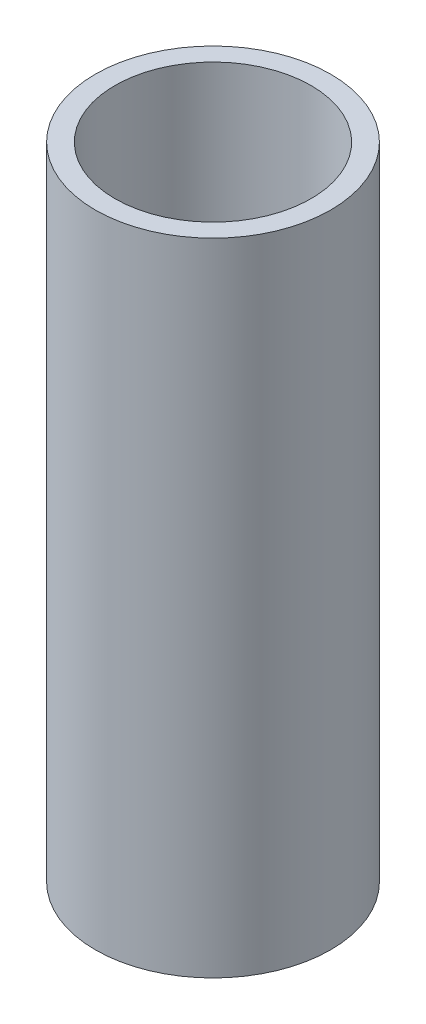
SolidWorks part; units mm, degrees
ref_plane "Front Plane" through (0, 0, 0) normal (0, 0, 1) x (1, 0, 0)
ref_plane "Top Plane" through (0, 0, 0) normal (0, 1, 0) x (1, 0, 0)
ref_plane "Right Plane" through (0, 0, 0) normal (1, 0, 0) x (0, 0, -1)
sketch "Sketch1" plane through (0, 0, 0) normal (0, 1, 0) x (1, 0, 0)
  circle A0 centre (0, 0) radius 9
  dimension "D1" = 18
extrude "Boss-Extrude1" add sketch "Sketch1" along normal blind 49 contours A0
sketch "Sketch2" plane through (0, 49, 0) normal (0, 1, 0) x (1, 0, 0)
  circle A0 centre (0, 0) radius 7.5
extrude "Cut-Extrude1" cut sketch "Sketch2" against normal blind 47 contours A0
